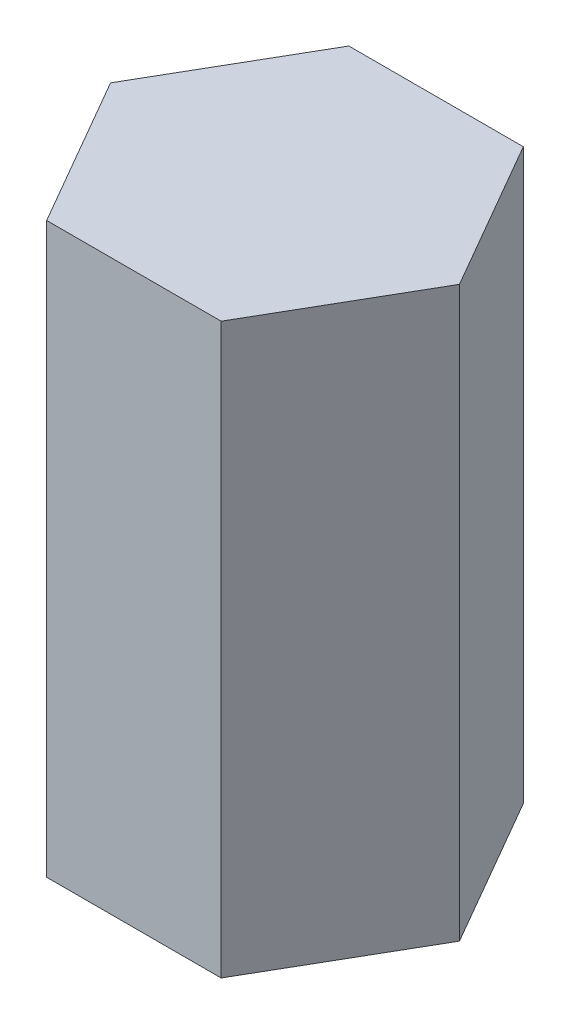
SolidWorks part; units mm, degrees
ref_plane "Front Plane" through (0, 0, 0) normal (0, 0, 1) x (1, 0, 0)
ref_plane "Top Plane" through (0, 0, 0) normal (0, 1, 0) x (1, 0, 0)
ref_plane "Right Plane" through (0, 0, 0) normal (1, 0, 0) x (0, 0, -1)
sketch "Sketch2" plane through (0, 0, 0) normal (0, 1, 0) x (1, 0, 0)
  line L1 (-9.815, 0) -> (-4.9075, -8.5)
  line L2 (-4.9075, -8.5) -> (4.9075, -8.5)
  line L3 (4.9075, -8.5) -> (9.815, 0)
  line L4 (9.815, 0) -> (4.9075, 8.5)
  line L5 (4.9075, 8.5) -> (-4.9075, 8.5)
  line L6 (-4.9075, 8.5) -> (-9.815, 0)
  circle A0 centre (0, 0) radius 8.5
  circle A1 centre (0, 0) radius 8.5 construction
extrude "Boss-Extrude1" add sketch "Sketch2" along normal blind 32 contours A0 L5 L6 | A0 L6 L1 | A0 L4 L5 | A0 | A0 L3 L4 | A0 L1 L2 | A0 L2 L3
